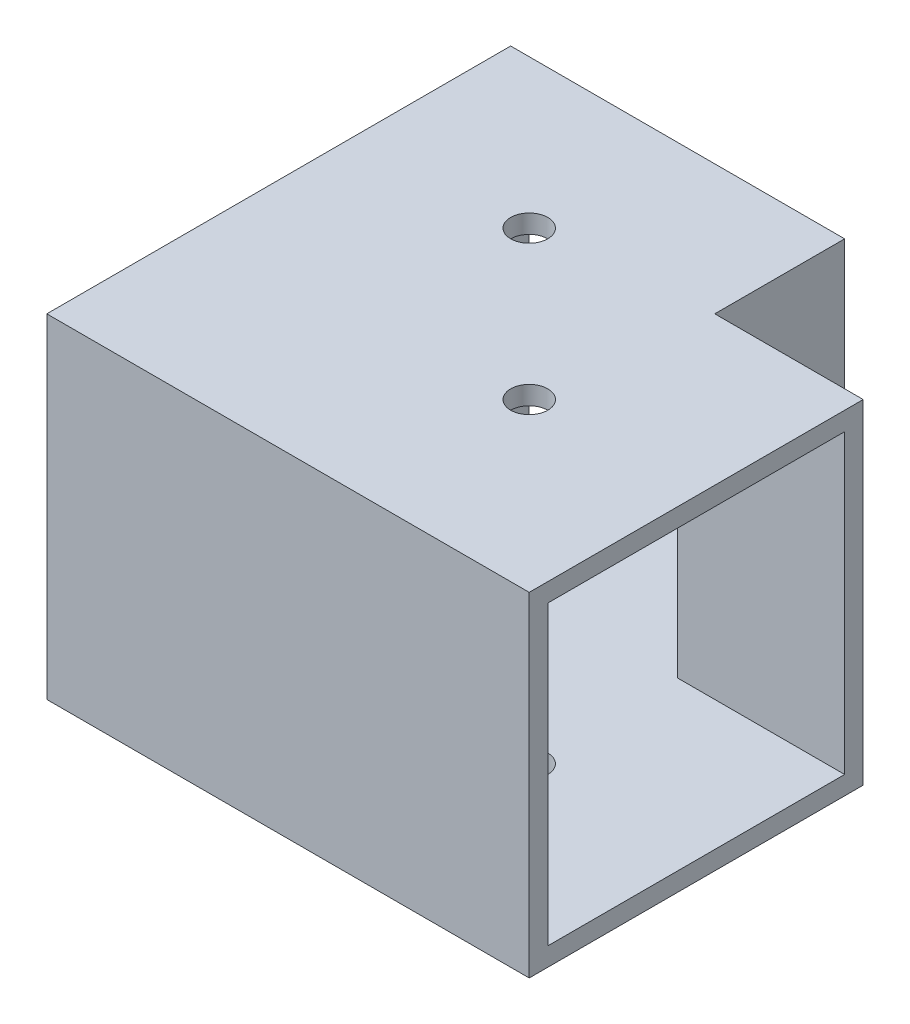
SolidWorks part; units mm, degrees
ref_plane "Front Plane" through (0, 0, 0) normal (0, 0, 1) x (1, 0, 0)
ref_plane "Top Plane" through (0, 0, 0) normal (0, 1, 0) x (1, 0, 0)
ref_plane "Right Plane" through (0, 0, 0) normal (1, 0, 0) x (0, 0, -1)
sketch "Sketch1" plane through (0, 0, 0) normal (0, 0, 1) x (1, 0, 0)
  line L1 (-50.8, -50.8) -> (50.8, -50.8)
  line L2 (-50.8, -50.8) -> (-50.8, 50.8)
  line L3 (-50.8, 50.8) -> (50.8, 50.8)
  line L4 (50.8, -50.8) -> (50.8, 50.8)
  line L5 (-50.8, -50.8) -> (50.8, 50.8) construction
  line L6 (-50.8, 50.8) -> (50.8, -50.8) construction
  point P0 (0, 0)
  dimension "D1" = 101.6
  dimension "D2" = 101.6
extrude "Extrude-Thin1" add sketch "Sketch1" along normal blind 50.8 thin
sketch "Sketch3" plane through (57.15, 0, 0) normal (1, 0, 0) x (0, 0, -1)
  line L0 (-50.8, 57.15) -> (0, 57.15) construction
  line L1 (-50.8, -50.8) -> (-152.4, -50.8)
  line L2 (-50.8, -50.8) -> (-50.8, 50.8)
  line L3 (-50.8, 50.8) -> (-152.4, 50.8)
  line L4 (-152.4, -50.8) -> (-152.4, 50.8)
  line L5 (-50.8, -57.15) -> (0, -57.15) construction
  line L6 (-50.8, -57.15) -> (-50.8, 57.15) construction
  dimension "D1" = 6.35
  dimension "D2" = 6.35
  dimension "D3" = 0
  dimension "D4" = 101.6
extrude "Extrude-Thin2" add sketch "Sketch3" along normal blind 50.8 thin thin type one direction wall 6.35
sketch "Sketch4" plane through (57.15, 0, 0) normal (-1, 0, 0) x (0, 0, 1)
  line L8 (50.8, -50.8) -> (50.8, -57.15)
  line L9 (50.8, -57.15) -> (158.75, -57.15)
  line L10 (158.75, -57.15) -> (158.75, 57.15)
  line L11 (158.75, 57.15) -> (50.8, 57.15)
  line L12 (50.8, 57.15) -> (50.8, 50.8)
  line L13 (50.8, 50.8) -> (152.4, 50.8)
  line L14 (152.4, 50.8) -> (152.4, -50.8)
  line L15 (152.4, -50.8) -> (50.8, -50.8)
  line L16 (50.8, -50.8) -> (50.8, -57.15)
  line L17 (50.8, -57.15) -> (158.75, -57.15)
  line L18 (158.75, -57.15) -> (158.75, 57.15)
  line L19 (158.75, 57.15) -> (50.8, 57.15)
  line L20 (50.8, 57.15) -> (50.8, 50.8)
  line L21 (50.8, 50.8) -> (152.4, 50.8)
  line L22 (152.4, 50.8) -> (152.4, -50.8)
  line L23 (152.4, -50.8) -> (50.8, -50.8)
  dimension "D1" = 0
extrude "Boss-Extrude1" add sketch "Sketch4" along normal up to surface (114.3 mm away) up to face at (-57.15, 0, 25.4)
sketch "Sketch6" plane through (0, 57.15, 0) normal (0, 1, 0) x (1, 0, 0)
  line L0 (0, 0) -> (0, -50.8) construction
  circle A0 centre (0, -50.8) radius 6.35
  dimension "D1" = 12.7
  dimension "D2" = 50.8
ref_plane "Plane1" through (50.8, 0, 50.8) normal (0.7071, 0, 0.7071) x (0.7071, 0, -0.7071)
extrude "Cut-Extrude1" cut sketch "Sketch6" against normal through all
mirror "Mirror1" about plane through (50.8, 0, 50.8) normal (0.7071, 0, 0.7071) of "Cut-Extrude1"
